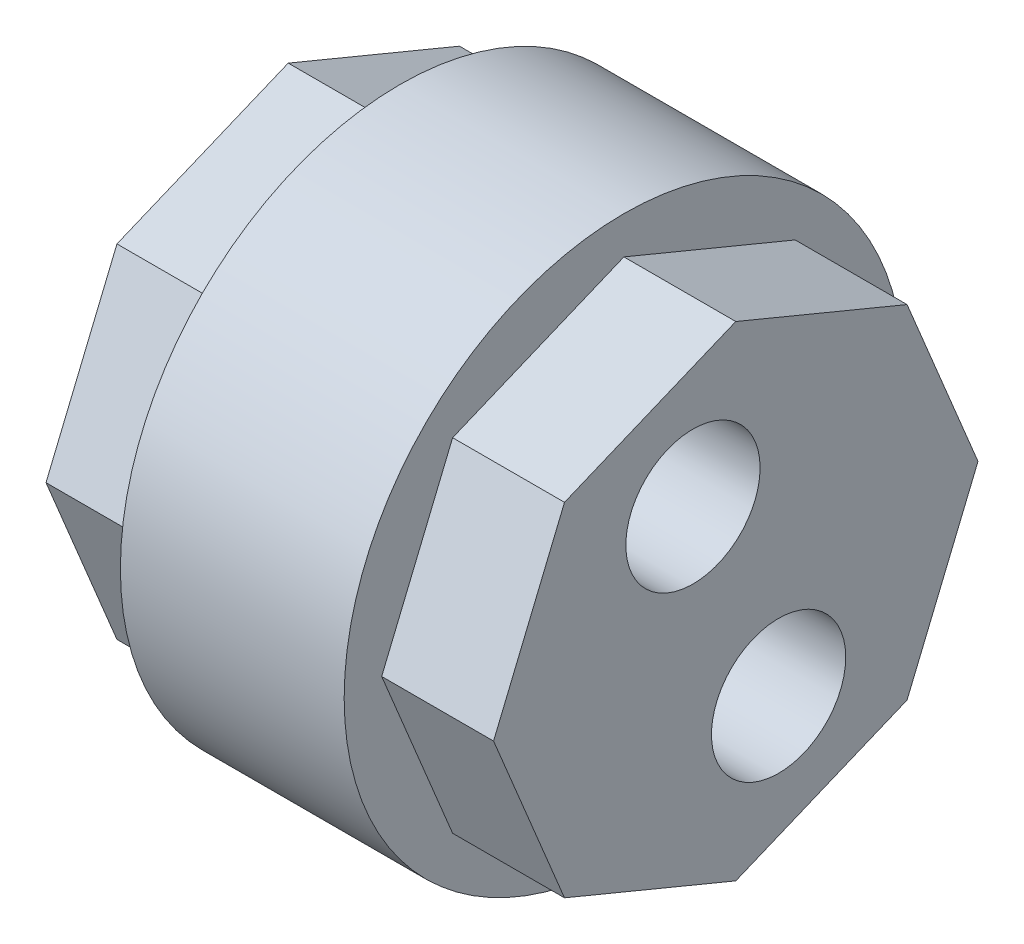
SolidWorks part; units mm, degrees
ref_plane "Front Plane" through (0, 0, 0) normal (0, 0, 1) x (1, 0, 0)
ref_plane "Top Plane" through (0, 0, 0) normal (0, 1, 0) x (1, 0, 0)
ref_plane "Right Plane" through (0, 0, 0) normal (1, 0, 0) x (0, 0, -1)
sketch "Sketch2" plane through (0, 0, 0) normal (1, 0, 0) x (0, 0, -1)
  circle A0 centre (0, 0) radius 12.5
  dimension "D1" = 25
extrude "Boss-Extrude1" add sketch "Sketch2" along normal blind 10
sketch "Sketch3" plane through (0, 0, 0) normal (-1, 0, 0) x (0, 0, 1)
  line L1 (10.8239, 0) -> (7.6537, 7.6537)
  line L2 (7.6537, 7.6537) -> (0, 10.8239)
  line L3 (0, 10.8239) -> (-7.6537, 7.6537)
  line L4 (-7.6537, 7.6537) -> (-10.8239, 0)
  line L5 (-10.8239, 0) -> (-7.6537, -7.6537)
  line L6 (-7.6537, -7.6537) -> (0, -10.8239)
  line L7 (0, -10.8239) -> (7.6537, -7.6537)
  line L8 (7.6537, -7.6537) -> (10.8239, 0)
  circle A0 centre (0, 0) radius 10 construction
  dimension "D1" = 20
extrude "Boss-Extrude3" add sketch "Sketch3" along normal blind 5 and the other way blind 15
sketch "Sketch4" plane through (-5, 0, 0) normal (-1, 0, 0) x (0, 0, 1)
  line L0 (3.8268, 9.2388) -> (-3.8268, -9.2388) construction
  line L1 (0, 10.8239) -> (7.6537, 7.6537) construction
  line L2 (0, -10.8239) -> (-7.6537, -7.6537) construction
  line L3 (9.2388, -3.8268) -> (-9.2388, 3.8268) construction
  line L4 (10.8239, 0) -> (7.6537, -7.6537) construction
  line L5 (-7.6537, 7.6537) -> (-10.8239, 0) construction
  line L6 (0, 0) -> (1.9134, 4.6194) construction
  line L7 (0, 0) -> (-1.9134, -4.6194) construction
  circle A0 centre (1.9134, 4.6194) radius 1
  circle A1 centre (-1.9134, -4.6194) radius 1
extrude "Cut-Extrude1" cut sketch "Sketch4" against normal blind 20
sketch "Sketch5" plane through (-5, 0, 0) normal (-1, 0, 0) x (0, 0, 1)
  circle A0 centre (-1.9134, -4.6194) radius 3
  circle A1 centre (1.9134, 4.6194) radius 3
extrude "Cut-Extrude2" cut sketch "Sketch5" against normal blind 5
sketch "Sketch6" plane through (15, 0, 0) normal (1, 0, 0) x (0, 0, -1)
  circle A0 centre (1.9134, -4.6194) radius 3
  circle A1 centre (-1.9134, 4.6194) radius 3
  dimension "D1" = 6
  dimension "D2" = 6
extrude "Cut-Extrude3" cut sketch "Sketch6" against normal blind 10
